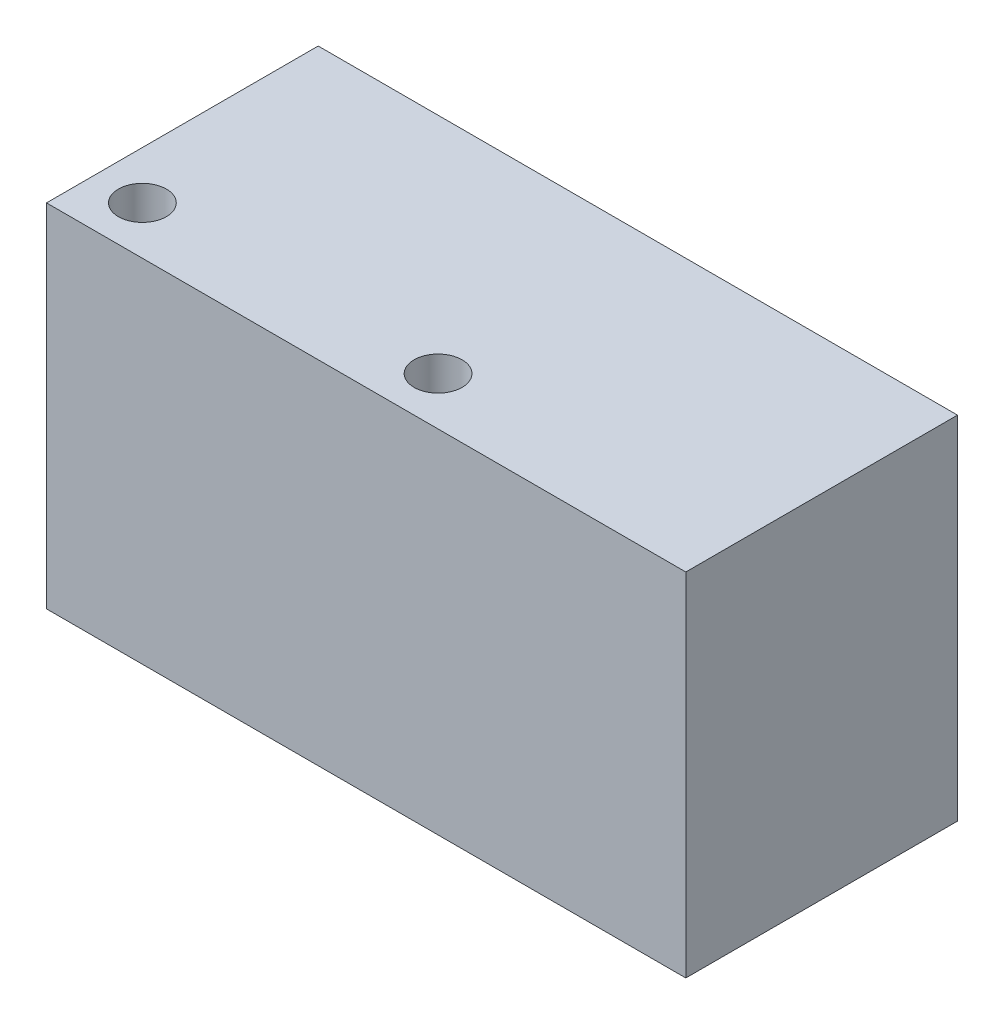
SolidWorks part; units mm, degrees
ref_plane "Front Plane" through (0, 0, 0) normal (0, 0, 1) x (1, 0, 0)
ref_plane "Top Plane" through (0, 0, 0) normal (0, 1, 0) x (1, 0, 0)
ref_plane "Right Plane" through (0, 0, 0) normal (1, 0, 0) x (0, 0, -1)
sketch "Sketch1" plane through (0, 0, 0) normal (0, 1, 0) x (1, 0, 0)
  line L1 (-20, 8.5) -> (20, 8.5)
  line L2 (-20, 8.5) -> (-20, -8.5)
  line L3 (-20, -8.5) -> (20, -8.5)
  line L4 (20, 8.5) -> (20, -8.5)
  line L5 (-20, 8.5) -> (20, -8.5) construction
  line L6 (-20, -8.5) -> (20, 8.5) construction
  point P0 (0, 0)
  dimension "D1" = 40
  dimension "D2" = 17
extrude "Boss-Extrude1" add sketch "Sketch1" along normal blind 22
sketch "Sketch2" plane through (0, 22, 0) normal (0, 1, 0) x (1, 0, 0)
  line L0 (-20, -8.5) -> (-20, -5.5) construction
  line L1 (-20, 8.5) -> (-20, -8.5) construction
  line L2 (-20, -5.5) -> (-17, -5.5) construction
  circle A0 centre (-17, -5.5) radius 1.5
  dimension "D3" = 3
  dimension "D1" = 3
  dimension "D2" = 3
extrude "Cut-Extrude1" cut sketch "Sketch2" against normal blind 22
sketch "Sketch3" plane through (0, 22, 0) normal (0, 1, 0) x (1, 0, 0)
  line L0 (-17, -5.5) -> (1.5, -5.5) construction
  circle A0 centre (1.5, -5.5) radius 1.5
  dimension "D2" = 3
  dimension "D1" = 18.5
extrude "Cut-Extrude2" cut sketch "Sketch3" against normal blind 22
